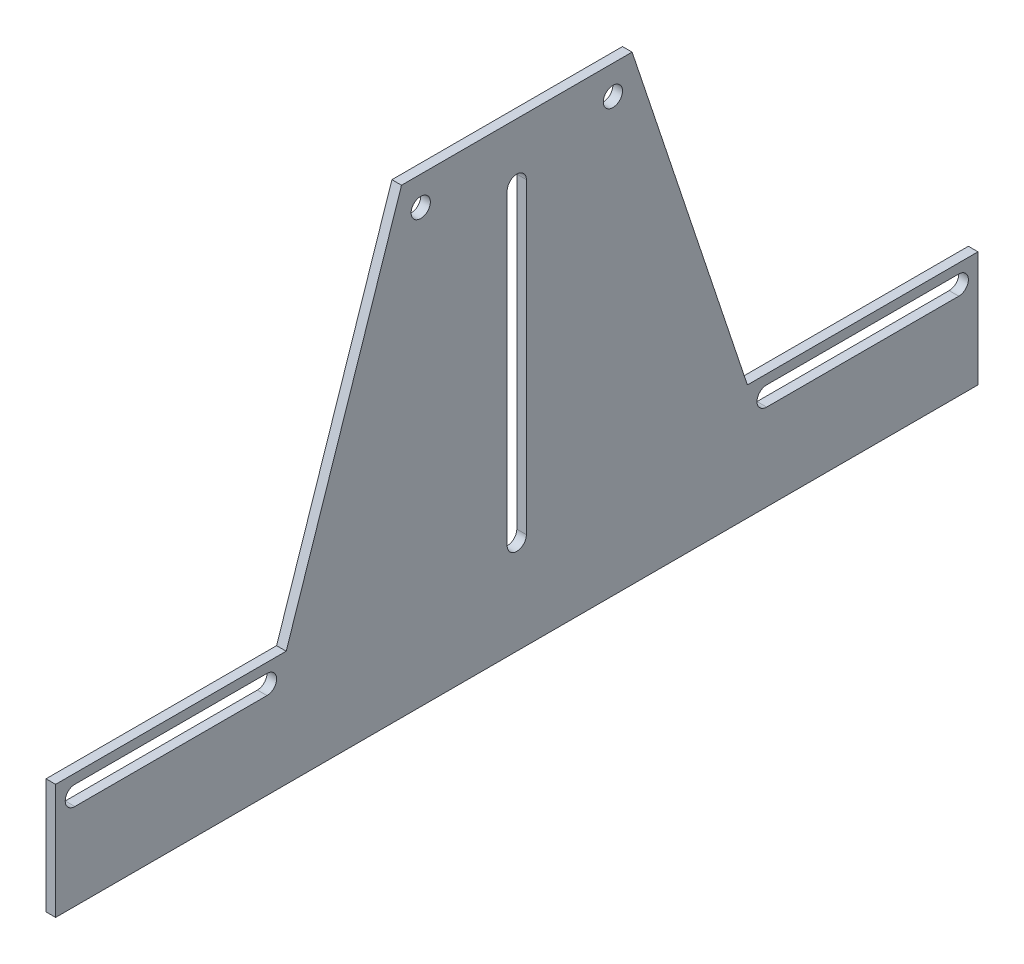
SolidWorks part; units mm, degrees
ref_plane "Front Plane" through (0, 0, 0) normal (0, 0, 1) x (1, 0, 0)
ref_plane "Top Plane" through (0, 0, 0) normal (0, 1, 0) x (1, 0, 0)
ref_plane "Right Plane" through (0, 0, 0) normal (1, 0, 0) x (0, 0, -1)
sketch "Sketch1" plane through (0, 0, 0) normal (1, 0, 0) x (0, 0, -1)
  line L0 (304.8, 0) -> (-304.8, 0)
  line L1 (-304.8, 0) -> (-304.8, 76.2)
  line L2 (-304.8, 76.2) -> (-152.4, 76.2)
  line L3 (-152.4, 76.2) -> (-76.2, 304.8)
  line L4 (-76.2, 304.8) -> (76.2, 304.8)
  line L5 (76.2, 304.8) -> (152.4, 76.2)
  line L6 (152.4, 76.2) -> (304.8, 76.2)
  line L7 (304.8, 76.2) -> (304.8, 0)
  line L8 (-292.1, 63.5) -> (-165.1, 63.5) construction
  line L9 (-292.1, 69.85) -> (-165.1, 69.85)
  line L10 (-292.1, 57.15) -> (-165.1, 57.15)
  line L11 (0, 445.048) -> (0, -191.0408) construction
  line L12 (292.1, 63.5) -> (165.1, 63.5) construction
  line L13 (292.1, 69.85) -> (165.1, 69.85)
  line L14 (292.1, 57.15) -> (165.1, 57.15)
  line L15 (0, 266.7) -> (0, 63.5) construction
  line L16 (6.35, 266.7) -> (6.35, 63.5)
  line L17 (-6.35, 266.7) -> (-6.35, 63.5)
  arc A0 (-292.1, 69.85) -> (-292.1, 57.15) centre (-292.1, 63.5) ccw
  arc A1 (-165.1, 57.15) -> (-165.1, 69.85) centre (-165.1, 63.5) ccw
  arc A2 (292.1, 69.85) -> (292.1, 57.15) centre (292.1, 63.5) cw
  arc A3 (165.1, 57.15) -> (165.1, 69.85) centre (165.1, 63.5) cw
  arc A4 (6.35, 266.7) -> (-6.35, 266.7) centre (0, 266.7) ccw
  arc A5 (-6.35, 63.5) -> (6.35, 63.5) centre (0, 63.5) ccw
  circle A6 centre (-63.5, 285.75) radius 6.35
  circle A7 centre (63.5, 285.75) radius 6.35
  point P3 (0, 0)
  point P12 (-228.6, 63.5)
  point P22 (228.6, 63.5)
  point P29 (0, 165.1)
  dimension "D9" = 12.7
  dimension "D10" = 38.1
  dimension "D11" = 12.7
  dimension "D1" = 609.6
  dimension "D2" = 152.4
  dimension "D3" = 152.4
  dimension "D4" = 152.4
  dimension "D5" = 76.2
  dimension "D6" = 304.8
  dimension "D7" = 76.2
  dimension "D8" = 76.2
  dimension "D12" = 19.05
  dimension "D14" = 63.5
extrude "Boss-Extrude1" add sketch "Sketch1" along normal blind 6.35
